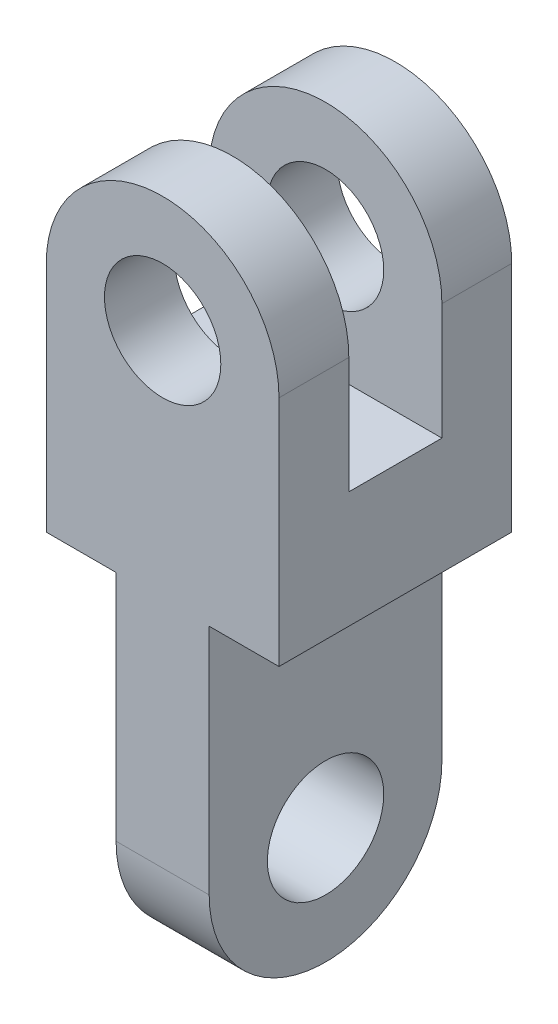
SolidWorks part; units mm, degrees
ref_plane "Ön Düzlem" through (0, 0, 0) normal (0, 0, 1) x (1, 0, 0)
ref_plane "Üst Düzlem" through (0, 0, 0) normal (0, 1, 0) x (1, 0, 0)
ref_plane "Sağ Düzlem" through (0, 0, 0) normal (1, 0, 0) x (0, 0, -1)
sketch "Sketch1" plane through (0, 0, 0) normal (1, 0, 0) x (0, 0, -1)
  line L1 (-63.7282, 8.2601) -> (36.2718, 8.2601)
  line L2 (-63.7282, 8.2601) -> (-63.7282, -91.7399)
  line L4 (36.2718, 8.2601) -> (36.2718, -91.7399)
  arc A0 (-63.7282, -91.7399) -> (36.2718, -91.7399) centre (-13.7282, -91.7399) ccw
  circle A1 centre (-13.7282, -91.7399) radius 25
extrude "Boss-Extrude1" add sketch "Sketch1" along normal blind 40
sketch "Sketch2" plane through (0, 0, 63.7282) normal (0, 0, 1) x (1, 0, 0)
  line L0 (20, 8.2601) -> (-30, 8.2601)
  line L1 (40, 8.2601) -> (0, 8.2601) construction
  line L2 (-30, 8.2601) -> (70, 8.2601)
  line L3 (70, 8.2601) -> (70, 108.2601)
  line L5 (-30, 108.2601) -> (-30, 8.2601)
  arc A0 (70, 108.2601) -> (-30, 108.2601) centre (20, 108.2601) ccw
  arc A1 (70, 108.2601) -> (-30, 108.2601) centre (20, 108.2601) ccw
  arc A2 (70, 108.2601) -> (-30, 108.2601) centre (20, 108.2601) ccw
  circle A3 centre (20, 108.2601) radius 25
  line M4 (40, 8.2601) -> (0, 8.2601)
extrude "Boss-Extrude2" add sketch "Sketch2" against normal blind 30 contours L3 A0 L5 L0 L2 A3 M4
sketch "Sketch4" plane through (40, 0, 0) normal (1, 0, 0) x (0, 0, -1)
  line L0 (-63.7282, 8.2601) -> (-13.7282, 8.2601)
  line L1 (36.2718, 8.2601) -> (-33.7282, 8.2601) construction
ref_plane "Plane1" through (0, 0, 13.7282) normal (0, 0, 1) x (1, 0, 0)
mirror "Mirror1" about plane through (0, 0, 13.7282) normal (0, 0, 1) of "Boss-Extrude2"
sketch "Sketch6" plane through (70, 0, 0) normal (1, 0, 0) x (0, 0, -1)
  line L0 (6.2718, 8.2601) -> (6.2718, 108.2601) construction
  line L1 (-33.7282, 8.2601) -> (6.2718, 8.2601)
  line L2 (-33.7282, 8.2601) -> (-33.7282, 58.2601)
  line L3 (-33.7282, 58.2601) -> (6.2718, 58.2601)
  line L4 (6.2718, 8.2601) -> (6.2718, 58.2601)
extrude "Boss-Extrude3" add sketch "Sketch6" against normal blind 100
